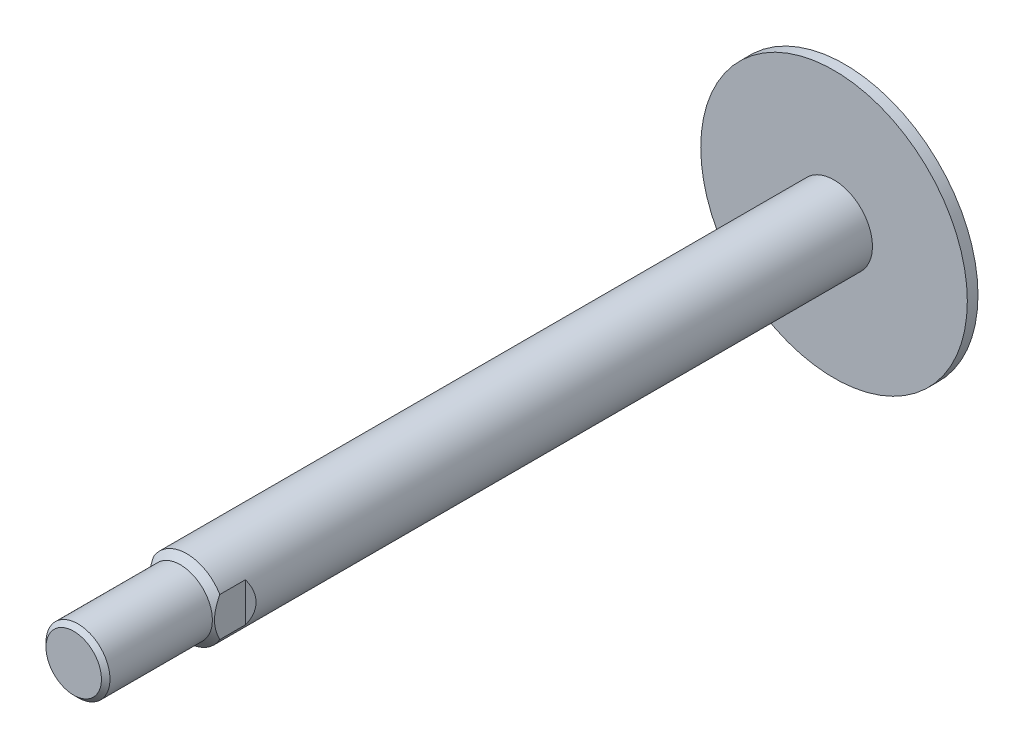
SolidWorks part; units mm, degrees
ref_plane "Front" through (0, 0, 0) normal (0, 0, 1) x (1, 0, 0)
ref_plane "Top" through (0, 0, 0) normal (0, 1, 0) x (1, 0, 0)
ref_plane "Right" through (0, 0, 0) normal (1, 0, 0) x (0, 0, -1)
sketch "Sketch1" plane through (0, 0, 0) normal (0, 0, 1) x (1, 0, 0)
  circle A0 centre (0, 0) radius 18
  dimension "D" = 36
extrude "Base-Extrude" add sketch "Sketch1" along normal blind 361.5
sketch "Sketch2" plane through (0, 0, 0) normal (0, 0, -1) x (-1, 0, 0)
  circle A0 centre (0, 0) radius 62.5
  dimension "Bore" = 125
extrude "Piston" add sketch "Sketch2" against normal blind 5
sketch "Sketch3" plane through (0, 0, 0) normal (1, 0, 0) x (0, 0, -1)
  line L0 (0, 0) -> (-197.6224, 0) construction
  line L1 (-361.5, 0) -> (-5, 0) construction
  line L2 (-361.5, 18) -> (-361.5, 13)
  line L3 (-361.5, 18) -> (-361.5, -18) construction
  line L4 (-361.5, 13) -> (-359.5, 15)
  line L5 (-359.5, 15) -> (-311.5, 15)
  line L6 (-311.5, 15) -> (-308.5, 18)
  line L7 (-308.5, 18) -> (-361.5, 18)
  line L8 (-5, 18) -> (-361.5, 18) construction
  dimension "D1" = 45
  dimension "MM" = 30
  dimension "D2" = 2
  dimension "A" = 50
revolve "Thread" cut sketch "Sketch3" angle 360 about L0
sketch "Sketch4" plane through (0, 0, 0) normal (0, 1, 0) x (1, 0, 0)
  line L0 (0, 0) -> (0, -184.8255) construction
  line L1 (0, -308.5) -> (0, -5) construction
  line L2 (18, -294) -> (15.5, -296.5)
  line L3 (15.5, -296.5) -> (15.5, -361.5)
  line L4 (15.5, -361.5) -> (18, -361.5)
  line L5 (18, -361.5) -> (18, -294)
  line L6 (18, -308.5) -> (18, -5) construction
  line L7 (-13, -361.5) -> (13, -361.5) construction
  line L8 (15, -311.5) -> (18, -308.5) construction
  line L9 (-15, -311.5) -> (15, -311.5) construction
  line L10 (-18, -361.5) -> (-18, -294)
  line L11 (-15.5, -361.5) -> (-18, -361.5)
  line L12 (-15.5, -296.5) -> (-15.5, -361.5)
  line L13 (-18, -294) -> (-15.5, -296.5)
  dimension "KA" = 31
  dimension "K" = 15
extrude "Flats" cut sketch "Sketch4" against normal through all and the other way through all
